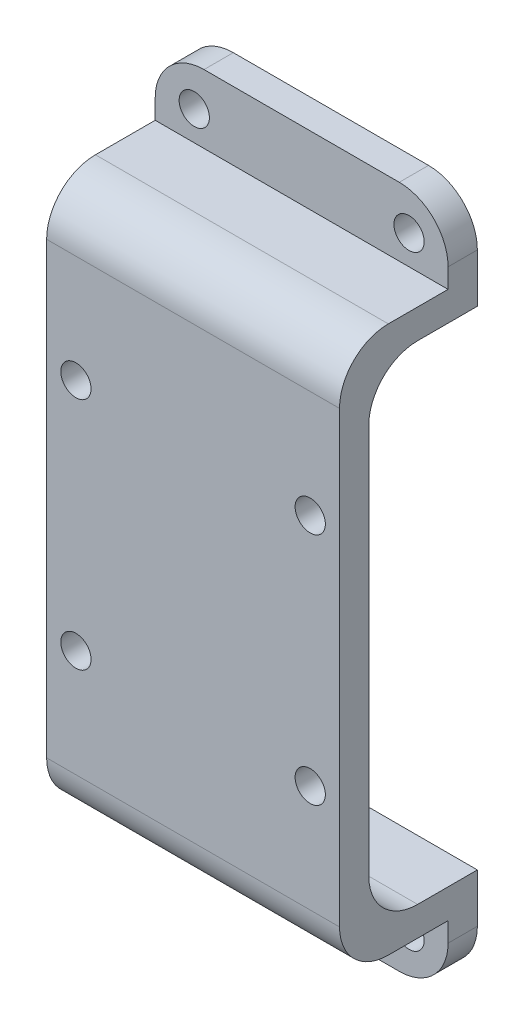
SolidWorks part; units mm, degrees
ref_plane "Alzado" through (0, 0, 0) normal (0, 0, 1) x (1, 0, 0)
ref_plane "Planta" through (0, 0, 0) normal (0, 1, 0) x (1, 0, 0)
ref_plane "Vista lateral" through (0, 0, 0) normal (1, 0, 0) x (0, 0, -1)
sketch "Croquis1" plane through (0, 0, 0) normal (0, 0, 1) x (1, 0, 0)
  line L1 (51.8935, -217.1) -> (111.8935, -217.1)
  line L2 (51.8935, -217.1) -> (51.8935, -227.1)
  line L3 (61.8935, -237.1) -> (101.8935, -237.1)
  line L4 (111.8935, -217.1) -> (111.8935, -227.1)
  line L5 (111.8935, -237.1) -> (111.8935, -97.1) construction
  line L14 (81.8935, -97.1) -> (81.8935, -237.1) construction
  line L21 (51.8935, -167.1) -> (111.8935, -167.1) construction
  line L22 (61.8935, -97.1) -> (101.8935, -97.1)
  line L23 (111.8935, -117.1) -> (111.8935, -107.1)
  line L24 (51.8935, -117.1) -> (111.8935, -117.1)
  line L25 (51.8935, -117.1) -> (51.8935, -107.1)
  line L26 (51.8935, -237.1) -> (111.8935, -237.1) construction
  line L27 (51.8935, -237.1) -> (51.8935, -97.1) construction
  line L28 (51.8935, -167.1) -> (111.8935, -167.1) construction
  arc A0 (101.8935, -97.1) -> (111.8935, -107.1) centre (101.8935, -107.1) cw
  arc A1 (101.8935, -237.1) -> (111.8935, -227.1) centre (101.8935, -227.1) ccw
  arc A2 (61.8935, -237.1) -> (51.8935, -227.1) centre (61.8935, -227.1) cw
  arc A9 (61.8935, -97.1) -> (51.8935, -107.1) centre (61.8935, -107.1) ccw
  circle A14 centre (59.8935, -105.1) radius 3.1
  circle A15 centre (103.8935, -105.1) radius 3.1
  circle A16 centre (59.8935, -229.1) radius 3.1
  circle A17 centre (103.8935, -229.1) radius 3.1
  dimension "D1" = 10
  dimension "D2" = 20
  dimension "D4" = 8
  dimension "D3" = 6.2
  dimension "D5" = 8
extrude "Saliente-Extruir1" add sketch "Croquis1" along normal blind 6
sketch "Croquis3" plane through (0, 0, 6) normal (0, 0, 1) x (1, 0, 0)
  line L12 (111.8935, -227.1) -> (111.8935, -217.1) construction
  line L17 (51.8935, -217.1) -> (111.8935, -217.1)
  line L18 (51.8935, -217.1) -> (51.8935, -223.1)
  line L31 (51.8935, -223.1) -> (111.8935, -223.1)
  line L32 (111.8935, -217.1) -> (111.8935, -223.1)
  line L37 (51.8935, -167.1) -> (111.8935, -167.1) construction
  line L38 (51.8935, -111.1) -> (111.8935, -111.1)
  line L39 (111.8935, -117.1) -> (111.8935, -111.1)
  line L40 (51.8935, -117.1) -> (111.8935, -117.1)
  line L41 (51.8935, -117.1) -> (51.8935, -111.1)
  point P6 (98.5022, -265)
  point P7 (38.5022, -265)
  dimension "D1" = 6
extrude "Saliente-Extruir2" add sketch "Croquis3" along normal blind 16.24
sketch "Croquis4" plane through (0, 0, 22.24) normal (0, 0, 1) x (1, 0, 0)
  line L0 (111.8935, -111.1) -> (51.8935, -111.1) construction
  line L1 (51.8935, -111.1) -> (111.8935, -111.1)
  line L2 (51.8935, -111.1) -> (51.8935, -223.1)
  line L3 (51.8935, -223.1) -> (111.8935, -223.1)
  line L4 (111.8935, -111.1) -> (111.8935, -223.1)
  line L5 (51.8935, -111.1) -> (51.8935, -117.1) construction
extrude "Saliente-Extruir3" add sketch "Croquis4" along normal blind 6
fillet "Redondeo1" radius 10 4 edges at (81.8935, -223.1, 28.24) (81.8935, -217.1, 22.24) (81.8935, -111.1, 28.24) (81.8935, -117.1, 22.24)
sketch "Croquis5" plane through (0, 0, 28.24) normal (0, 0, 1) x (1, 0, 0)
  arc A0 (103.7015, -193.292) -> (108.0855, -188.908) centre (105.8935, -191.1) ccw construction
  arc A1 (55.7015, -188.908) -> (60.0855, -193.292) centre (57.8935, -191.1) ccw construction
  arc A2 (60.0855, -140.908) -> (55.7015, -145.292) centre (57.8935, -143.1) ccw construction
  arc A3 (108.0855, -145.292) -> (103.7015, -140.908) centre (105.8935, -143.1) ccw construction
  circle A4 centre (105.8935, -143.1) radius 3.1
  circle A5 centre (105.8935, -191.1) radius 3.1
  circle A6 centre (57.8935, -191.1) radius 3.1
  arc A12 (103.7015, -193.292) -> (108.0855, -188.908) centre (105.8935, -191.1) ccw construction
  arc A13 (55.7015, -188.908) -> (60.0855, -193.292) centre (57.8935, -191.1) ccw construction
  arc A14 (60.0855, -140.908) -> (55.7015, -145.292) centre (57.8935, -143.1) ccw construction
  arc A15 (108.0855, -145.292) -> (103.7015, -140.908) centre (105.8935, -143.1) ccw construction
  circle A20 centre (57.8935, -143.1) radius 3.1
extrude "Cortar-Extruir1" cut sketch "Croquis5" against normal through all
equation "\"Grosor\"= 6mm"
equation "\"D1@Saliente-Extruir1\"=\"Grosor\""
equation "\"D1@Saliente-Extruir3\"=\"Grosor\""
